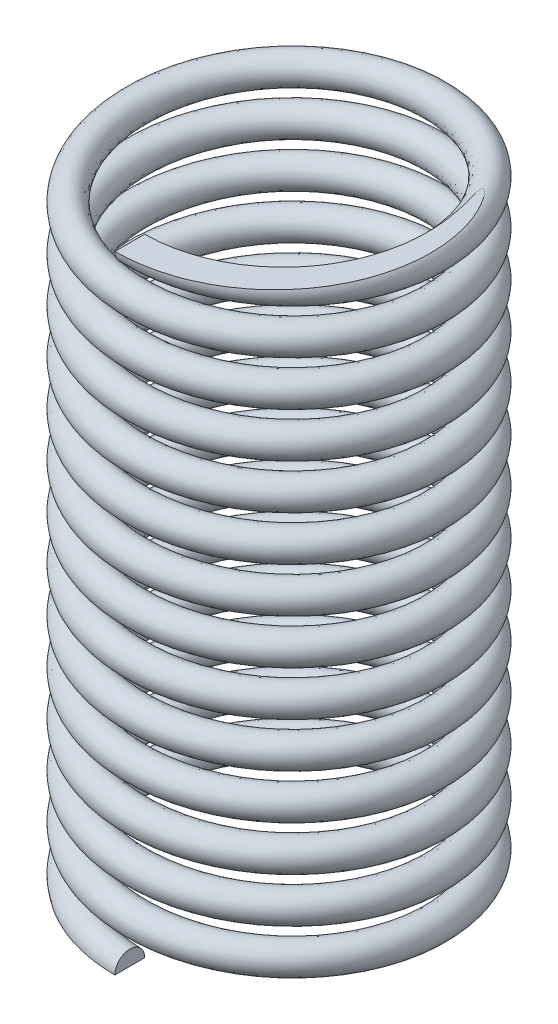
SolidWorks part; units mm, degrees
ref_plane "Front Plane" through (0, 0, 0) normal (0, 0, 1) x (1, 0, 0)
ref_plane "Top Plane" through (0, 0, 0) normal (0, 1, 0) x (1, 0, 0)
ref_plane "Right Plane" through (0, 0, 0) normal (1, 0, 0) x (0, 0, -1)
sketch "Sketch2" plane through (0, 0, 0) normal (0, 1, 0) x (1, 0, 0)
  circle A0 centre (0, 0) radius 2.5
  dimension "D1" = 5
curve "Helix/Spiral1" pitch 0.75 height 10.5 turns 14
sketch "Sketch3" plane through (0, 0, 0) normal (1, 0, 0) x (0, 0, -1)
  line L0 (0, 0) -> (-2.5, 0) construction
  circle A0 centre (-2.5, 0) radius 0.25
  dimension "D2" = 0.5
  dimension "D1" = 2.5
sweep "Sweep1" add profiles "Sketch3" path "Helix/Spiral1"
sketch "Sketch4" plane through (0, 0, 0) normal (1, 0, 0) x (0, 0, -1)
  line L0 (3, -0.5) -> (3, 10.5) construction
  line L1 (3, 0) -> (-3, 0)
  line L2 (3, 0) -> (3, -0.5)
  line L3 (3, -0.5) -> (-3, -0.5)
  line L4 (-3, 0) -> (-3, -0.5)
  line L6 (3, 10.5) -> (-3, 10.5)
  line L7 (3, 10.5) -> (3, 11)
  line L8 (3, 11) -> (-3, 11)
  line L9 (-3, 10.5) -> (-3, 11)
  dimension "D1" = 6
  dimension "D2" = 0.5
  dimension "D3" = 0.5
  dimension "D4" = 3
  dimension "D5" = 11
  dimension "D6" = 6
  dimension "D7" = 0.5
extrude "Cut-Extrude1" cut sketch "Sketch4" against normal through all both and the other way through all
